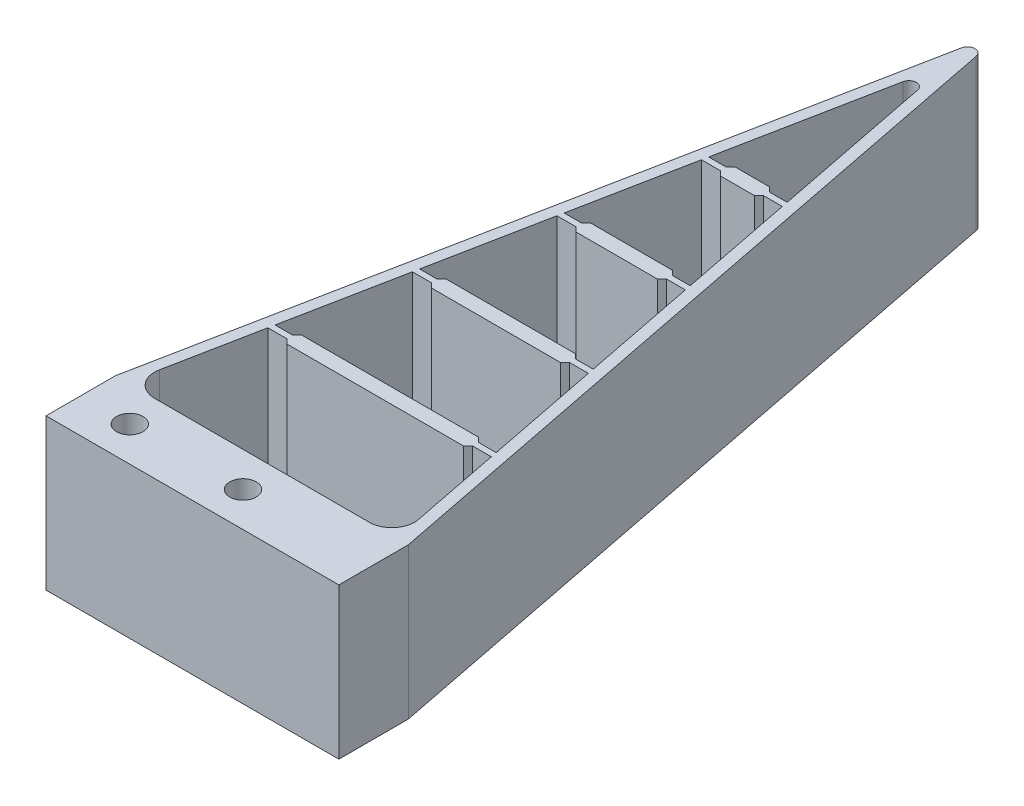
SolidWorks part; units mm, degrees
material "POM Acetal Copolymer"
ref_plane "Front" through (0, 0, 0) normal (0, 0, 1) x (1, 0, 0)
ref_plane "Top" through (0, 0, 0) normal (0, 1, 0) x (1, 0, 0)
ref_plane "Right" through (0, 0, 0) normal (1, 0, 0) x (0, 0, -1)
sketch "Sketch1" plane through (0, 0, 0) normal (0, 1, 0) x (1, 0, 0)
  line L0 (-19.4, 0) -> (19.4, 0)
  line L1 (-19.4, 0) -> (-19.4, 9.2)
  line L2 (-19.4, 9.2) -> (0, 107.7976)
  line L3 (0, 107.7976) -> (19.4, 9.2)
  line L4 (19.4, 9.2) -> (19.4, 0)
  dimension "D1" = 38.8
  dimension "D2" = 9.2
  dimension "D3" = 107.7976
extrude "Boss-Extrude1" add sketch "Sketch1" along normal mid plane 20
fillet "Fillet1" radius 0.987 1 edges at (0, 0, -107.7976)
sketch "Sketch2" plane through (0, 0, 0) normal (0, 1, 0) x (1, 0, 0)
  line L4 (-17.8712, 9.2) -> (17.8712, 9.2)
  line L5 (-19.4, 0) -> (19.4, 0) construction
  line L6 (17.9282, 8.9104) -> (0, 100.0279)
  line L7 (0, 100.0279) -> (-17.9282, 8.9104)
  line L8 (17.8712, 9.2) -> (0.9665, 95.1159)
  line L9 (-0.9665, 95.1159) -> (-17.8712, 9.2)
  line L10 (-19.4, 0) -> (19.4, 0) construction
  line L11 (-14.9198, 24.2) -> (14.9198, 24.2)
  line L12 (14.5263, 26.2) -> (-14.5263, 26.2)
  line L13 (-11.7717, 40.2) -> (11.7717, 40.2)
  line L14 (11.3782, 42.2) -> (-11.3782, 42.2)
  line L15 (-8.6235, 56.2) -> (8.6235, 56.2)
  line L16 (8.23, 58.2) -> (-8.23, 58.2)
  line L17 (-5.4754, 72.2) -> (5.4754, 72.2)
  line L18 (5.0819, 74.2) -> (-5.0819, 74.2)
  arc A2 (-0.9665, 95.1159) -> (0.9665, 95.1159) centre (0, 94.9258) cw
  dimension "D2" = 0.985
  dimension "D3" = 9.2
  dimension "D4" = 2
  dimension "D5" = 15
  dimension "D6" = 4
  dimension "D7" = 14
  dimension "D1" = 1.5
extrude "Cut-Extrude1" cut sketch "Sketch2" against normal through all and the other way through all contours L11 L9 L4 L8 | L13 L9 L12 L8 | L15 L9 L14 L8 | L17 L9 L16 L8 | A2 L9 L18 L8
sketch "Sketch3" plane through (0, 10, 0) normal (0, 1, 0) x (1, 0, 0)
  line L0 (-19.4, 0) -> (19.4, 0) construction
  line L1 (-19.4, 9.2) -> (-19.4, 0) construction
  circle A0 centre (-12.9, 4.6) radius 1.75
  circle A1 centre (2.1, 4.6) radius 1.75
  dimension "D1" = 3.5
  dimension "D2" = 4.6
  dimension "D3" = 6.5
  dimension "D4" = 15
extrude "Cut-Extrude2" cut sketch "Sketch3" against normal through all and the other way through all
sketch "Sketch4" plane through (0, 0, 0) normal (0, 1, 0) x (1, 0, 0)
  line L0 (17.8712, 9.2) -> (14.9198, 24.2) construction
  line L1 (-17.8712, 9.2) -> (17.8712, 9.2) construction
  line L2 (14.5263, 26.2) -> (11.7717, 40.2) construction
  line L3 (-11.7717, 40.2) -> (11.7717, 40.2) construction
  line L4 (-11.7717, 40.2) -> (-14.5263, 26.2) construction
  line L5 (19.4, 9.2) -> (0.9684, 102.8757)
  line L6 (-0.9684, 102.8757) -> (-19.4, 9.2)
  line L7 (-19.4, 9.2) -> (-19.4, 0)
  line L8 (-19.4, 0) -> (19.4, 0)
  line L9 (19.4, 0) -> (19.4, 9.2)
  line L10 (19.4, 9.2) -> (0.9684, 102.8757)
  line L11 (-0.9684, 102.8757) -> (-19.4, 9.2)
  line L12 (-19.4, 9.2) -> (-19.4, 0)
  line L13 (-19.4, 0) -> (19.4, 0)
  line L14 (19.4, 0) -> (19.4, 9.2)
  line L15 (14.5263, 26.2) -> (-14.5263, 26.2) construction
  line L16 (-14.9198, 24.2) -> (-17.8712, 9.2) construction
  line L17 (-14.9198, 24.2) -> (14.9198, 24.2) construction
  line L18 (14.5263, 26.2) -> (11.7717, 40.2)
  line L19 (-11.7717, 40.2) -> (11.7717, 40.2)
  line L20 (-11.7717, 40.2) -> (-14.5263, 26.2)
  line L21 (14.5263, 26.2) -> (-14.5263, 26.2)
  line L22 (-17.8712, 9.2) -> (17.8712, 9.2)
  line L23 (-14.9198, 24.2) -> (-17.8712, 9.2)
  line L24 (-14.9198, 24.2) -> (14.9198, 24.2)
  line L25 (17.8712, 9.2) -> (14.9198, 24.2)
  line L26 (5.0819, 74.2) -> (0.9665, 95.1159) construction
  line L27 (-0.9665, 95.1159) -> (-5.0819, 74.2) construction
  line L28 (5.0819, 74.2) -> (-5.0819, 74.2) construction
  line L29 (-5.4754, 72.2) -> (5.4754, 72.2) construction
  line L30 (-5.4754, 72.2) -> (-8.23, 58.2) construction
  line L31 (8.23, 58.2) -> (-8.23, 58.2) construction
  line L32 (8.23, 58.2) -> (5.4754, 72.2) construction
  line L33 (11.3782, 42.2) -> (8.6235, 56.2) construction
  line L34 (11.3782, 42.2) -> (-11.3782, 42.2) construction
  line L35 (-8.6235, 56.2) -> (8.6235, 56.2) construction
  line L36 (-8.6235, 56.2) -> (-11.3782, 42.2) construction
  line L37 (5.0819, 74.2) -> (0.9665, 95.1159)
  line L38 (-0.9665, 95.1159) -> (-5.0819, 74.2)
  line L39 (5.0819, 74.2) -> (-5.0819, 74.2)
  line L40 (-5.4754, 72.2) -> (5.4754, 72.2)
  line L41 (-5.4754, 72.2) -> (-8.23, 58.2)
  line L42 (8.23, 58.2) -> (-8.23, 58.2)
  line L43 (8.23, 58.2) -> (5.4754, 72.2)
  line L44 (11.3782, 42.2) -> (8.6235, 56.2)
  line L45 (11.3782, 42.2) -> (-11.3782, 42.2)
  line L46 (-8.6235, 56.2) -> (8.6235, 56.2)
  line L47 (-8.6235, 56.2) -> (-11.3782, 42.2)
  line L48 (14.9198, 24.2) -> (14.5263, 26.2)
  line L49 (11.7717, 40.2) -> (11.3782, 42.2)
  line L50 (8.6235, 56.2) -> (8.23, 58.2)
  line L51 (5.4754, 72.2) -> (5.0819, 74.2)
  line L52 (-5.0819, 74.2) -> (-5.4754, 72.2)
  line L53 (-8.23, 58.2) -> (-8.6235, 56.2)
  line L54 (-11.3782, 42.2) -> (-11.7717, 40.2)
  line L55 (-14.5263, 26.2) -> (-14.9198, 24.2)
  line L56 (14.6444, 25.6) -> (12.3018, 25.6)
  line L57 (12.3018, 25.6) -> (11.7018, 26.2)
  line L58 (14.8018, 24.8) -> (12.3018, 24.8)
  line L59 (12.3018, 24.8) -> (11.7018, 24.2)
  line L60 (-14.7231, 25.2) -> (14.7231, 25.2) construction
  line L61 (-11.5749, 41.2) -> (11.5749, 41.2) construction
  line L62 (-8.4268, 57.2) -> (8.4268, 57.2) construction
  line L63 (-5.2786, 73.2) -> (5.2786, 73.2) construction
  line L64 (11.4962, 41.6) -> (9.1536, 41.6)
  line L65 (9.1536, 41.6) -> (8.5536, 42.2)
  line L66 (11.6536, 40.8) -> (9.1536, 40.8)
  line L67 (9.1536, 40.8) -> (8.5536, 40.2)
  line L68 (5.4055, 56.2) -> (6.0055, 56.8)
  line L69 (6.0055, 56.8) -> (8.5055, 56.8)
  line L70 (8.3481, 57.6) -> (6.0055, 57.6)
  line L71 (6.0055, 57.6) -> (5.4055, 58.2)
  line L72 (5.3573, 72.8) -> (2.8573, 72.8)
  line L73 (2.8573, 72.8) -> (2.2573, 72.2)
  line L74 (2.2573, 74.2) -> (2.8573, 73.6)
  line L75 (2.8573, 73.6) -> (5.1999, 73.6)
  line L76 (0, 0) -> (0, 102.6851) construction
  line L77 (-2.2573, 74.2) -> (-2.8573, 73.6)
  line L78 (-2.8573, 73.6) -> (-5.1999, 73.6)
  line L79 (-5.3573, 72.8) -> (-2.8573, 72.8)
  line L80 (-2.8573, 72.8) -> (-2.2573, 72.2)
  line L81 (-6.0055, 57.6) -> (-5.4055, 58.2)
  line L82 (-8.3481, 57.6) -> (-6.0055, 57.6)
  line L83 (-6.0055, 56.8) -> (-8.5055, 56.8)
  line L84 (-5.4055, 56.2) -> (-6.0055, 56.8)
  line L85 (-11.4962, 41.6) -> (-9.1536, 41.6)
  line L86 (-9.1536, 41.6) -> (-8.5536, 42.2)
  line L87 (-9.1536, 40.8) -> (-8.5536, 40.2)
  line L88 (-11.6536, 40.8) -> (-9.1536, 40.8)
  line L89 (-14.6444, 25.6) -> (-12.3018, 25.6)
  line L90 (-12.3018, 25.6) -> (-11.7018, 26.2)
  line L91 (-12.3018, 24.8) -> (-11.7018, 24.2)
  line L92 (-14.8018, 24.8) -> (-12.3018, 24.8)
  arc A0 (0.9665, 95.1159) -> (-0.9665, 95.1159) centre (0, 94.9258) ccw construction
  arc A1 (0.9684, 102.8757) -> (-0.9684, 102.8757) centre (0, 102.6851) ccw
  arc A2 (0.9684, 102.8757) -> (-0.9684, 102.8757) centre (0, 102.6851) ccw
  arc A3 (0.9665, 95.1159) -> (-0.9665, 95.1159) centre (0, 94.9258) ccw
  dimension "D4" = 0.8
  dimension "D2" = 135
  dimension "D3" = 2.5
  dimension "D5" = 0.8
  dimension "D6" = 0.8
  dimension "D7" = 0.8
  dimension "D1" = 0
extrude "Cut-Extrude3" cut sketch "Sketch4" against normal through all and the other way through all contours L58 L59 L24 L48 | L57 L56 L48 L21 | L89 L90 L21 L55 | L92 L55 L24 L91 | L85 L86 L45 L54 | L88 L54 L19 L87 | L66 L67 L19 L49 | L65 L64 L49 L45 | L69 L68 L46 L50 | L71 L70 L50 L42 | L53 L82 L81 L42 | L46 L84 L83 L53 | L72 L73 L40 L51 | L74 L75 L51 L39 | L78 L77 L39 L52 | L80 L79 L52 L40
fillet "Fillet2" radius 3 2 edges at (17.8712, 0, -9.2) (-17.8712, 0, -9.2)
equation "\"D5@Sketch4\"=\"D4@Sketch4\""
equation "\"D6@Sketch4\"=\"D4@Sketch4\""
equation "\"D7@Sketch4\"=\"D4@Sketch4\""
